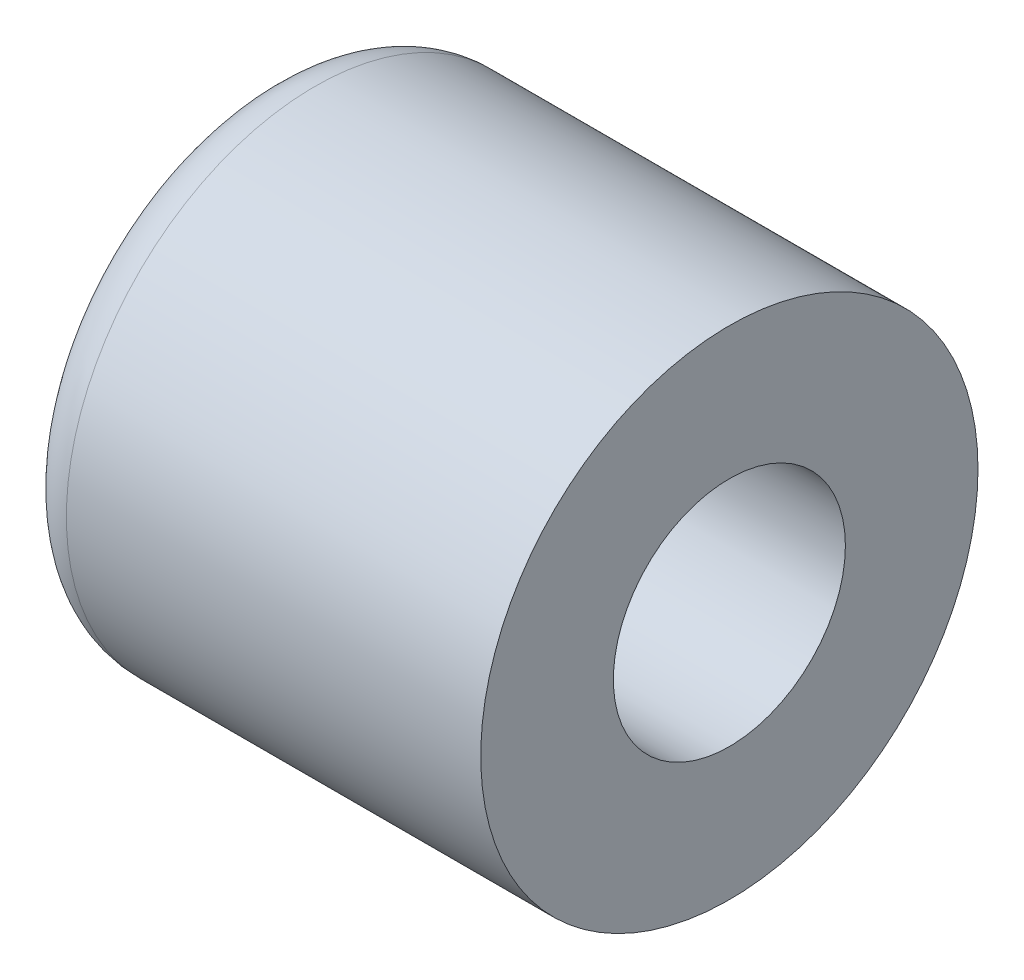
SolidWorks part; units mm, degrees
ref_plane "Front Plane" through (0, 0, 0) normal (0, 0, 1) x (1, 0, 0)
ref_plane "Top Plane" through (0, 0, 0) normal (0, 1, 0) x (1, 0, 0)
ref_plane "Right Plane" through (0, 0, 0) normal (1, 0, 0) x (0, 0, -1)
sketch "Sketch1" plane through (0, 0, 0) normal (1, 0, 0) x (0, 0, -1)
  line L0 (0, 0) -> (0, 50000) construction
  line L1 (0, 0) -> (50000, 0) construction
  circle A0 centre (0, 0) radius 7.5
extrude "Boss-Extrude1" add sketch "Sketch1" along normal mid plane 14
hole_wizard "M8x1.0 Tapped Hole1" positions "Sketch2" profile "Sketch3" tap size "M8x1.0" standard "ANSI Metric"
sketch "Sketch2" plane through (7, 0, 0) normal (1, 0, 0) x (0, 0, -1)
  point P0 (0, 0)
sketch "Sketch3" plane through (7, 0, 0) normal (0, 1, 0) x (0, 0, -1)
  line L0 (0, 0) -> (0, 12.103)
  line L1 (0, 12.103) -> (3.5, 10)
  line L2 (3.5, 10) -> (3.5, 0)
  line L5 (3.5, 0) -> (0, 0)
  line L10 (0, 12.103) -> (-3.5, 10) construction
  line L11 (0, -6.35) -> (0, 107.95) construction
  dimension "Tap Drill Dia." = 7
  dimension "Tap Drill Depth" = 10
  dimension "Drill Angle" = 118
cosmetic thread "Hole Thread1" parameters "D1"=16, "D2"=8
fillet "Fillet1" radius 1.5 1 edges at (-7, 0, -7.5)
